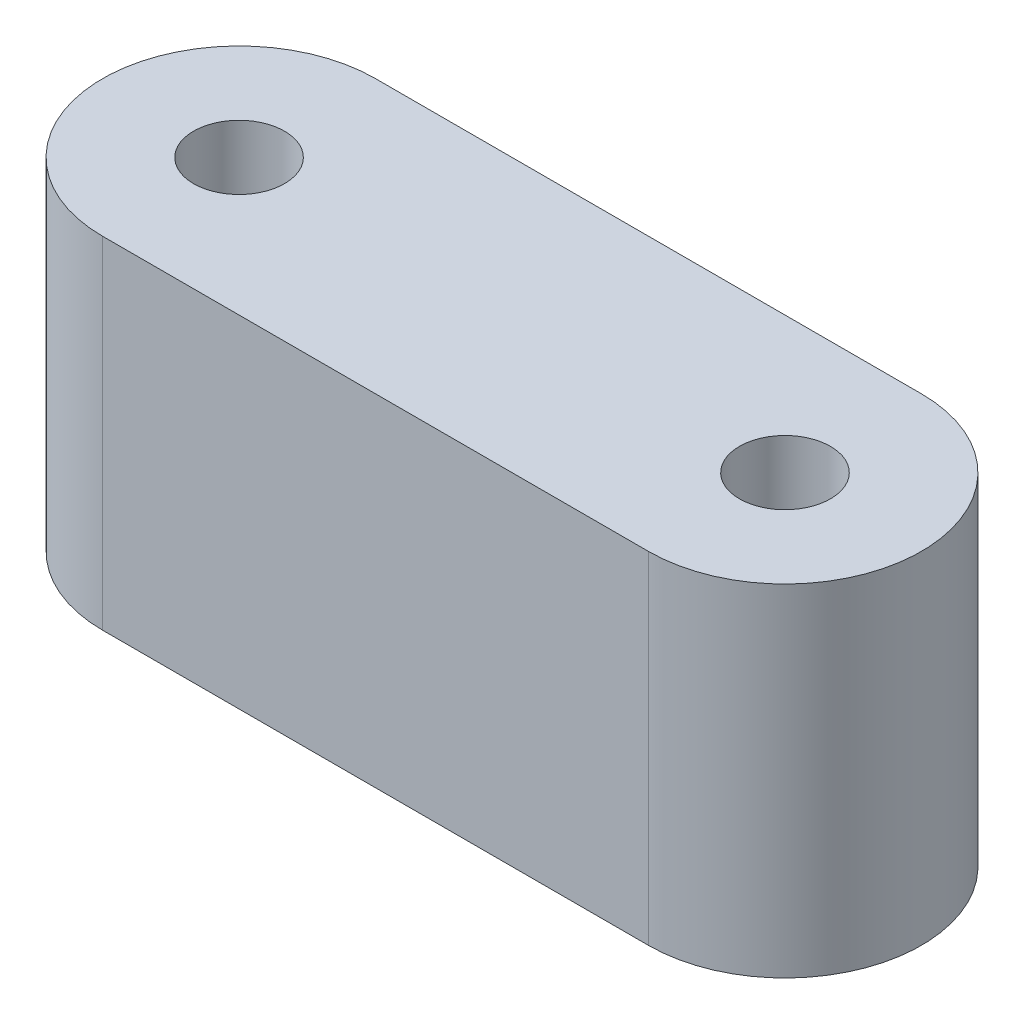
SolidWorks part; units mm, degrees
material "ABS"
ref_plane "Front Plane" through (0, 0, 0) normal (0, 0, 1) x (1, 0, 0)
ref_plane "Top Plane" through (0, 0, 0) normal (0, 1, 0) x (1, 0, 0)
ref_plane "Right Plane" through (0, 0, 0) normal (1, 0, 0) x (0, 0, -1)
sketch "Sketch1" plane through (0, 0, 0) normal (0, 1, 0) x (1, 0, 0)
  line L0 (-12, 0) -> (12, 0) construction
  line L1 (-12, 0) -> (12, 0) construction
  line L2 (-12, 6) -> (12, 6)
  line L3 (-12, -6) -> (12, -6)
  circle A0 centre (-12, 0) radius 2
  circle A1 centre (12, 0) radius 2
  arc A2 (-12, 6) -> (-12, -6) centre (-12, 0) ccw
  arc A3 (12, -6) -> (12, 6) centre (12, 0) ccw
  point P6 (0, 0)
  dimension "D2" = 4
  dimension "D3" = 4
  dimension "D1" = 24
extrude "Boss-Extrude1" add sketch "Sketch1" along normal blind 15
